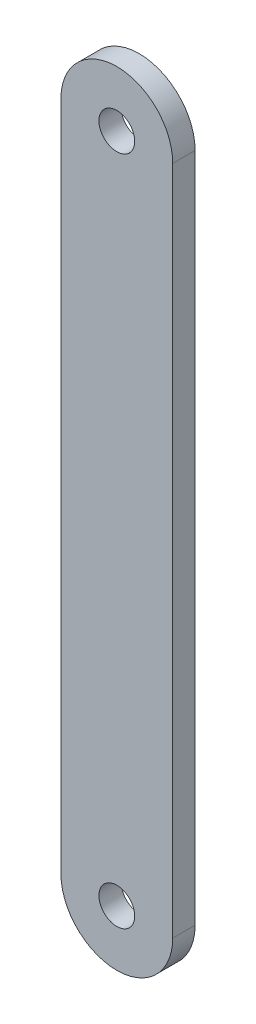
SolidWorks part; units mm, degrees
ref_plane "前视基准面" through (0, 0, 0) normal (0, 0, 1) x (1, 0, 0)
ref_plane "上视基准面" through (0, 0, 0) normal (0, 1, 0) x (1, 0, 0)
ref_plane "右视基准面" through (0, 0, 0) normal (1, 0, 0) x (0, 0, -1)
sketch "草图1" plane through (0, 0, 0) normal (0, 0, 1) x (1, 0, 0)
  line L0 (0, -30) -> (0, 30) construction
  line L1 (-5, -30) -> (-5, 30)
  line L2 (5, -30) -> (5, 30)
  line L3 (-1000, 0) -> (49000, 0) construction
  arc A0 (-5, -30) -> (5, -30) centre (0, -30) ccw
  arc A1 (5, 30) -> (-5, 30) centre (0, 30) ccw
  circle A2 centre (0, 30) radius 1.6
  circle A3 centre (0, -30) radius 1.6
  point P2 (0, 0)
  dimension "D3" = 3.2
  dimension "D1" = 60
  dimension "D2" = 10
extrude "凸台-拉伸1" add sketch "草图1" along normal blind 2
